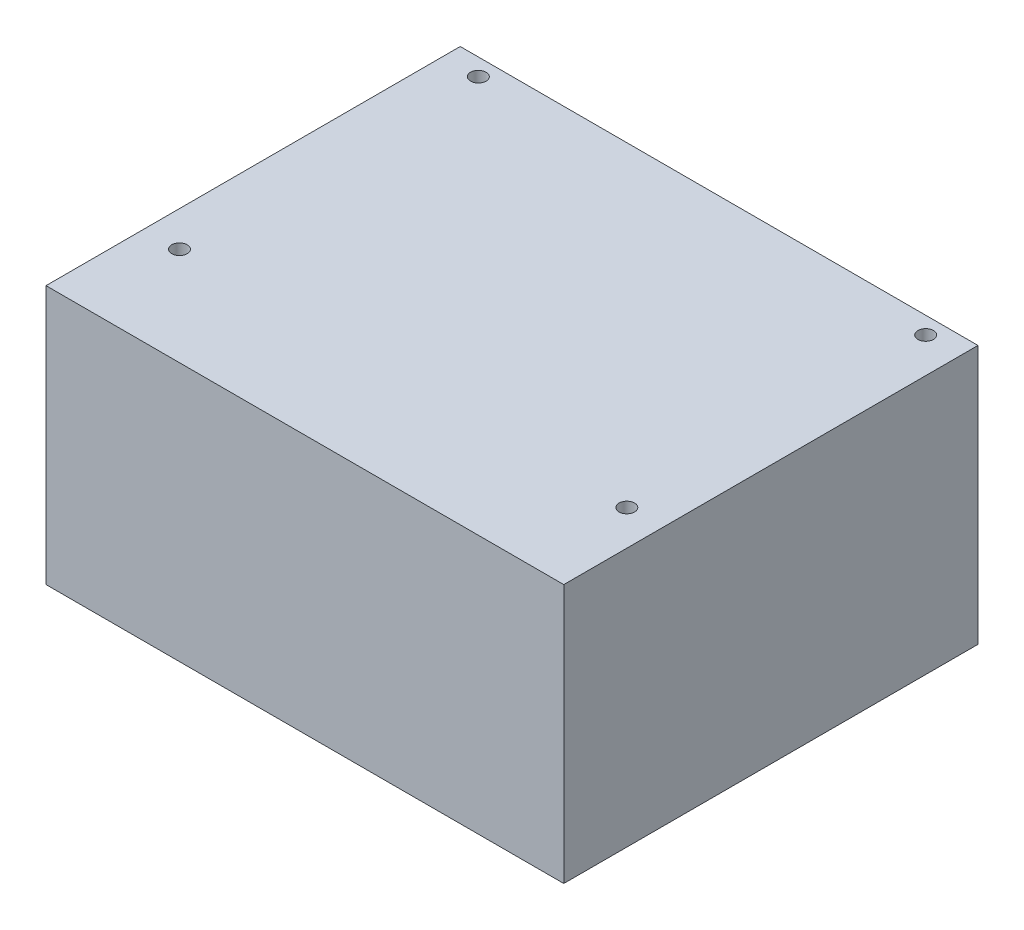
SolidWorks part; units mm, degrees
ref_plane "前视基准面" through (0, 0, 0) normal (0, 0, 1) x (1, 0, 0)
ref_plane "上视基准面" through (0, 0, 0) normal (0, 1, 0) x (1, 0, 0)
ref_plane "右视基准面" through (0, 0, 0) normal (1, 0, 0) x (0, 0, -1)
sketch "草图1" plane through (0, 0, 0) normal (0, 1, 0) x (1, 0, 0)
  line L1 (-50, 40) -> (50, 40)
  line L2 (-50, 40) -> (-50, -40)
  line L3 (-50, -40) -> (50, -40)
  line L4 (50, 40) -> (50, -40)
  line L5 (-50, 40) -> (50, -40) construction
  line L6 (-50, -40) -> (50, 40) construction
  point P0 (0, 0)
  dimension "D1" = 100
  dimension "D2" = 80
extrude "凸台-拉伸1" add sketch "草图1" along normal blind 50
sketch "草图2" plane through (0, 50, 0) normal (0, 1, 0) x (1, 0, 0)
  line L0 (0, 40) -> (0, -40) construction
  line L1 (-43.2, 36.7) -> (43.2, 36.7) construction
  line L2 (-43.2, 36.7) -> (-43.2, -21.02) construction
  line L3 (-43.2, -21.02) -> (43.2, -21.02) construction
  line L4 (43.2, 36.7) -> (43.2, -21.02) construction
  line L5 (-43.2, 36.7) -> (43.2, -21.02) construction
  line L6 (-43.2, -21.02) -> (43.2, 36.7) construction
  line L7 (50, 40) -> (-50, 40) construction
  line L8 (-50, -40) -> (50, -40) construction
  line L9 (-50, 0) -> (50, 0) construction
  line L10 (-50, 40) -> (-50, -40) construction
  line L11 (50, -40) -> (50, 40) construction
  line L12 (-43.2, 7.84) -> (43.2, 7.84) construction
  circle A0 centre (43.2, 36.7) radius 1.5
  circle A1 centre (-43.2, 36.7) radius 1.5
  circle A2 centre (43.2, -21.02) radius 1.5
  circle A3 centre (-43.2, -21.02) radius 1.5
  point P0 (0, 7.84)
  dimension "D4" = 3
  dimension "D1" = 86.4
  dimension "D2" = 57.72
  dimension "D3" = 3.3
extrude "切除-拉伸1" cut sketch "草图2" against normal blind 50
